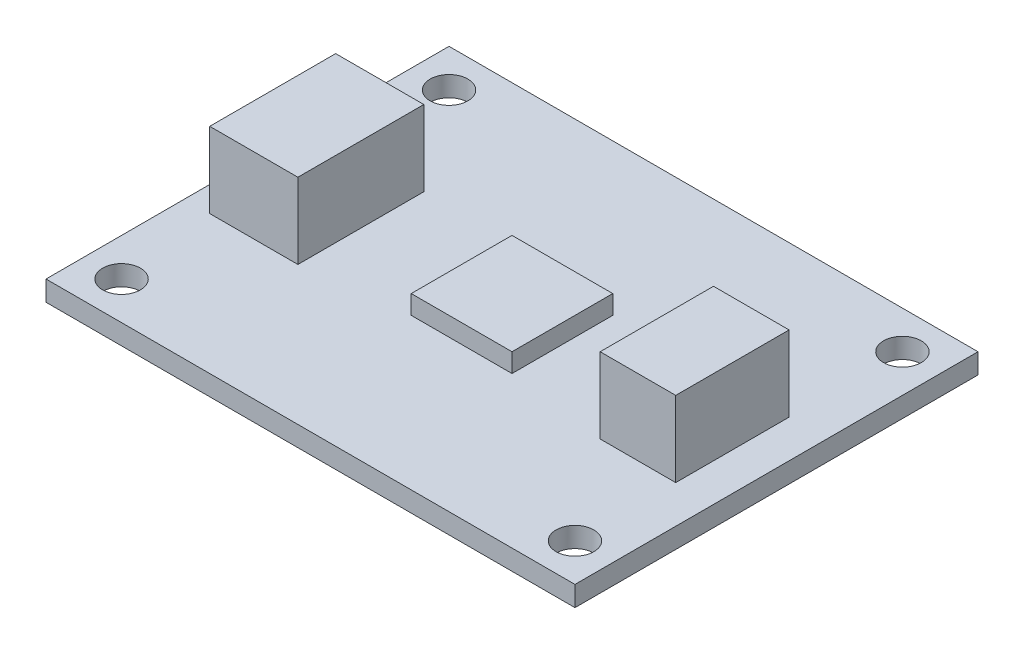
SolidWorks part; units mm, degrees
ref_plane "Front Plane" through (0, 0, 0) normal (0, 0, 1) x (1, 0, 0)
ref_plane "Top Plane" through (0, 0, 0) normal (0, 1, 0) x (1, 0, 0)
ref_plane "Right Plane" through (0, 0, 0) normal (1, 0, 0) x (0, 0, -1)
other "Configuration Table"
sketch "Sketch1" plane through (0, 0, 0) normal (0, 1, 0) x (1, 0, 0)
  line L1 (0, 0) -> (42, 0)
  line L2 (0, 0) -> (0, 32)
  line L3 (0, 32) -> (42, 32)
  line L4 (42, 0) -> (42, 32)
extrude "PCB" add sketch "Sketch1" along normal blind 1.6
sketch "Sketch2" plane through (0, 0, 0) normal (0, 1, 0) x (1, 0, 0)
  circle A0 centre (3, 3) radius 1.5
extrude "Mount_hole_1" cut sketch "Sketch2" against normal through all and the other way through all
sketch "Sketch3" plane through (0, 0, 0) normal (0, 1, 0) x (1, 0, 0)
  circle A0 centre (39, 3) radius 1.5
extrude "Mount_hole_2" cut sketch "Sketch3" against normal through all and the other way through all
sketch "Sketch4" plane through (0, 0, 0) normal (0, 1, 0) x (1, 0, 0)
  circle A0 centre (3, 29) radius 1.5
extrude "Mount_hole_3" cut sketch "Sketch4" against normal through all and the other way through all
sketch "Sketch5" plane through (0, 0, 0) normal (0, 1, 0) x (1, 0, 0)
  circle A0 centre (39, 29) radius 1.5
extrude "Mount_hole_4" cut sketch "Sketch5" against normal through all and the other way through all
sketch "Sketch6" plane through (0, 0, 0) normal (0, 1, 0) x (1, 0, 0)
  line L1 (2, 11) -> (9, 11)
  line L2 (2, 11) -> (2, 21)
  line L3 (2, 21) -> (9, 21)
  line L4 (9, 11) -> (9, 21)
extrude "Probe_connector_XH" add sketch "Sketch6" along normal blind 6 from offset 1.6
sketch "Sketch7" plane through (0, 0, 0) normal (0, 1, 0) x (1, 0, 0)
  line L1 (33, 11) -> (39, 11)
  line L2 (33, 11) -> (33, 20)
  line L3 (33, 20) -> (39, 20)
  line L4 (39, 11) -> (39, 20)
extrude "Signal_connector_PH" add sketch "Sketch7" along normal blind 6 from offset 1.6
sketch "Sketch8" plane through (0, 0, 0) normal (0, 1, 0) x (1, 0, 0)
  line L1 (17, 12) -> (25, 12)
  line L2 (17, 12) -> (17, 20)
  line L3 (17, 20) -> (25, 20)
  line L4 (25, 12) -> (25, 20)
extrude "Signal_IC" add sketch "Sketch8" along normal blind 1.5 from offset 1.6
